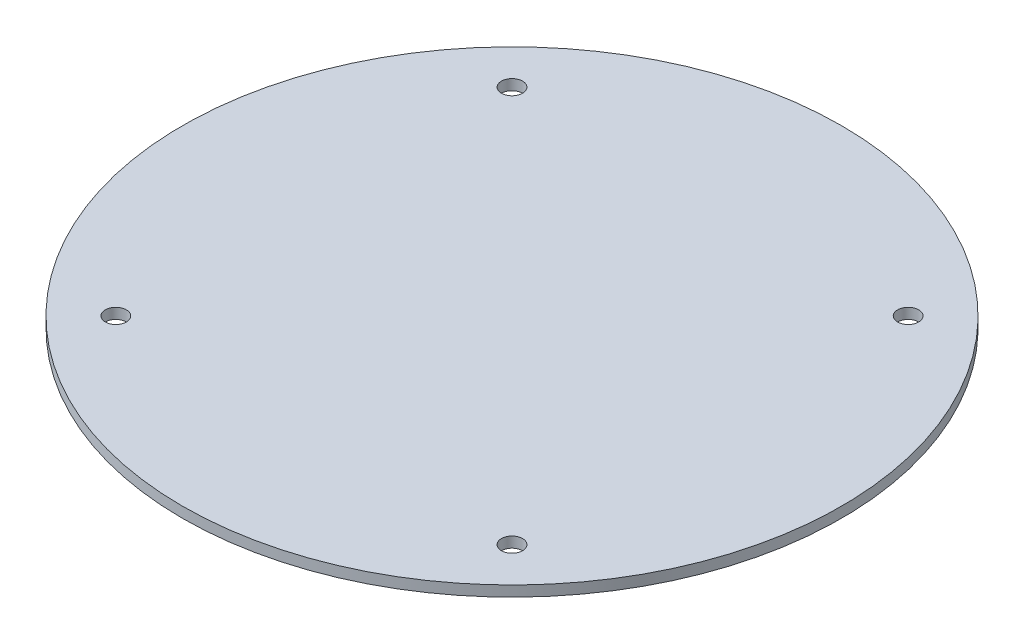
SolidWorks part; units mm, degrees
ref_plane "Plano frontal" through (0, 0, 0) normal (0, 0, 1) x (1, 0, 0)
ref_plane "Plano superior" through (0, 0, 0) normal (0, 1, 0) x (1, 0, 0)
ref_plane "Plano direito" through (0, 0, 0) normal (1, 0, 0) x (0, 0, -1)
sketch "Esboço1" plane through (0, 0, 0) normal (0, 1, 0) x (1, 0, 0)
  circle A0 centre (0, 0) radius 50
  dimension "D1" = 100
extrude "Ressalto-extrusão1" add sketch "Esboço1" along normal blind 1.6
sketch "Esboço2" plane through (0, 0, 0) normal (0, -1, 0) x (1, 0, 0)
  line L0 (0, 0) -> (-42.5, 0) construction
  line L1 (-30.052, -30.052) -> (0, 0) construction
  line L2 (0, 0) -> (-30.052, -30.052) construction
  circle A0 centre (-30.052, -30.052) radius 1.6
  circle A1 centre (0, 0) radius 42.5 construction
  circle A2 centre (-30.052, 30.052) radius 1.6
  circle A3 centre (30.052, 30.052) radius 1.6
  circle A4 centre (30.052, -30.052) radius 1.6
  dimension "D1" = 3.2
  dimension "D2" = 85
  dimension "D3" = 45
  dimension "D5" = 42.5
  dimension "D6" = 30.052
  dimension "D4" = 4
extrude "Corte-extrusão1" cut sketch "Esboço2" against normal through all
